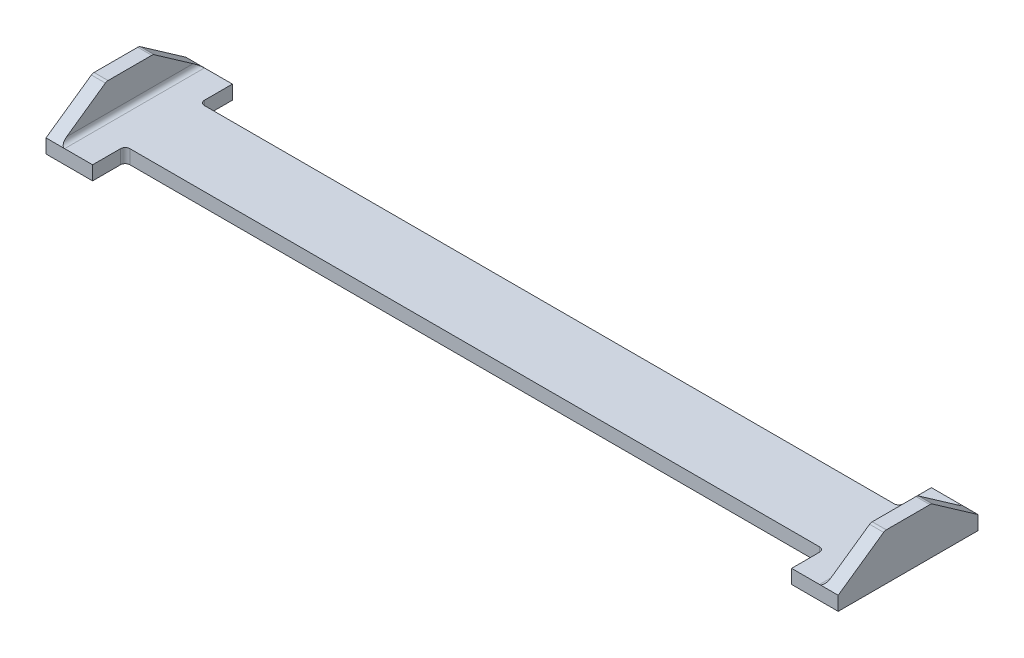
SolidWorks part; units mm, degrees
ref_plane "Front Plane" through (0, 0, 0) normal (0, 0, 1) x (1, 0, 0)
ref_plane "Top Plane" through (0, 0, 0) normal (0, 1, 0) x (1, 0, 0)
ref_plane "Right Plane" through (0, 0, 0) normal (1, 0, 0) x (0, 0, -1)
sketch "Sketch1" plane through (0, 0, 0) normal (0, 1, 0) x (1, 0, 0)
  line L0 (0, 0) -> (38744.0864, 0) construction
  line L1 (0, 0) -> (0, 38744.0864) construction
  line L2 (95.25, 10.16) -> (-95.25, 10.16)
  line L3 (-95.25, 10.16) -> (-95.25, 19.05)
  line L4 (-95.25, 19.05) -> (-107.95, 19.05)
  line L5 (-107.95, 19.05) -> (-107.95, -19.05)
  line L6 (-95.25, -19.05) -> (-107.95, -19.05)
  line L7 (-95.25, -10.16) -> (-95.25, -19.05)
  line L8 (95.25, -10.16) -> (-95.25, -10.16)
  line L9 (95.25, -10.16) -> (95.25, -19.05)
  line L10 (95.25, -19.05) -> (107.95, -19.05)
  line L11 (107.95, 19.05) -> (107.95, -19.05)
  line L12 (95.25, 19.05) -> (107.95, 19.05)
  line L13 (95.25, 10.16) -> (95.25, 19.05)
  point P5 (107.95, 0)
  point P11 (-107.95, 0)
  point P15 (0, -10.16)
  point P20 (0, 10.16)
  dimension "D1" = 20.32
  dimension "D2" = 38.1
  dimension "D3" = 215.9
  dimension "D4" = 190.5
extrude "Boss-Extrude1" add sketch "Sketch1" along normal blind 3.81
sketch "Sketch2" plane through (-107.95, 0, 0) normal (-1, 0, 0) x (0, 0, 1)
  line L0 (-19.05, 0) -> (-19.05, 3.81)
  line L1 (-19.05, 3.81) -> (-6.35, 12.7)
  line L2 (0, 0) -> (0, 12.7) construction
  line L3 (-19.05, 0) -> (19.05, 0) construction
  line L4 (-6.35, 12.7) -> (6.35, 12.7)
  line L5 (19.05, 3.81) -> (6.35, 12.7)
  line L6 (19.05, 0) -> (19.05, 3.81)
  line L7 (-19.05, 0) -> (19.05, 0)
  dimension "D1" = 12.7
  dimension "D2" = 12.7
extrude "Boss-Extrude2" add sketch "Sketch2" against normal blind 3.81
mirror "Mirror1" about plane through (0, 0, 0) normal (1, 0, 0) of "Boss-Extrude2"
fillet "Fillet1" radius 1.27 6 edges at (106.045, 12.7, -6.35) (106.045, 12.7, 6.35) (-106.045, 12.7, -6.35) (-106.045, 12.7, 6.35) (104.14, 3.81, 0) (-104.14, 3.81, 0)
fillet "Fillet2" radius 1.27 4 edges at (95.25, 1.905, -10.16) (95.25, 1.905, 10.16) (-95.25, 1.905, -10.16) (-95.25, 1.905, 10.16)
